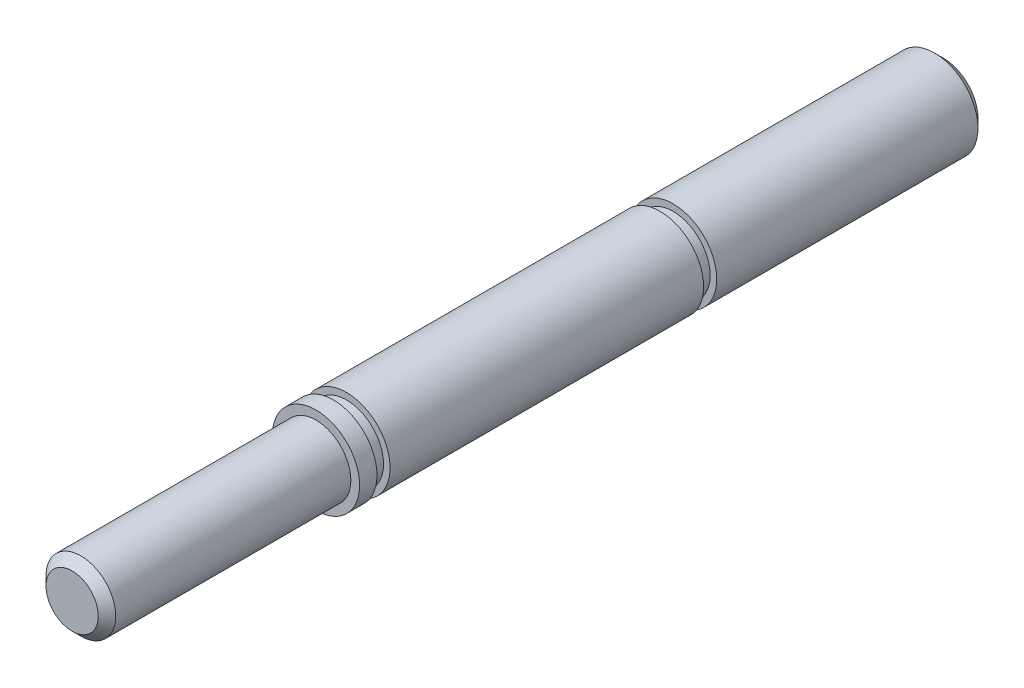
SolidWorks part; units mm, degrees
material "AISI 1020"
ref_plane "Alzado" through (0, 0, 0) normal (0, 0, 1) x (1, 0, 0)
ref_plane "Planta" through (0, 0, 0) normal (0, 1, 0) x (1, 0, 0)
ref_plane "Vista lateral" through (0, 0, 0) normal (1, 0, 0) x (0, 0, -1)
sketch "Croquis1" plane through (0, 0, 0) normal (0, 0, 1) x (1, 0, 0)
  circle A0 centre (0, 0) radius 5
  dimension "D1" = 10
extrude "Saliente-Extruir1" add sketch "Croquis1" along normal mid plane 100
chamfer "Chaflán1" distance 1 angle 45 1 edges at (5, 0, -50)
sketch "Croquis4" plane through (0, 0, 0) normal (0, 1, 0) x (1, 0, 0)
  line L0 (5, -50) -> (5, 49) construction
  line L1 (4.25, 19) -> (5.75, 19)
  line L2 (4.25, 19) -> (4.25, 17.5)
  line L3 (4.25, 17.5) -> (5.75, 17.5)
  line L4 (5.75, 19) -> (5.75, 17.5)
  line L5 (4.25, 19) -> (5.75, 17.5) construction
  line L6 (4.25, 17.5) -> (5.75, 19) construction
  line L7 (4, 50) -> (-4, 50) construction
  line L8 (0, 0) -> (0, 65.1631) construction
  line L9 (5, -50) -> (5, 49) construction
  line L10 (4.25, -18.5) -> (5.75, -18.5)
  line L11 (4.25, -18.5) -> (4.25, -20)
  line L12 (4.25, -20) -> (5.75, -20)
  line L13 (5.75, -18.5) -> (5.75, -20)
  line L14 (4.25, -18.5) -> (5.75, -20) construction
  line L15 (4.25, -20) -> (5.75, -18.5) construction
  point P0 (5, 18.25)
  point P12 (5, -19.25)
  dimension "D1" = 1.5
  dimension "D2" = 31
  dimension "D3" = 1.5
  dimension "D4" = 36
revolve "Cortar-Revolución2" cut sketch "Croquis4" angle 360 about L8
sketch "Croquis5" plane through (0, 0, 50) normal (0, 0, 1) x (1, 0, 0)
  circle A0 centre (0, 0) radius 4
  dimension "D1" = 8
extrude "Cortar-Extruir2" cut sketch "Croquis5" against normal blind 28 flip side to cut
chamfer "Chaflán3" distance 1 angle 45 1 edges at (4, 0, 50)
